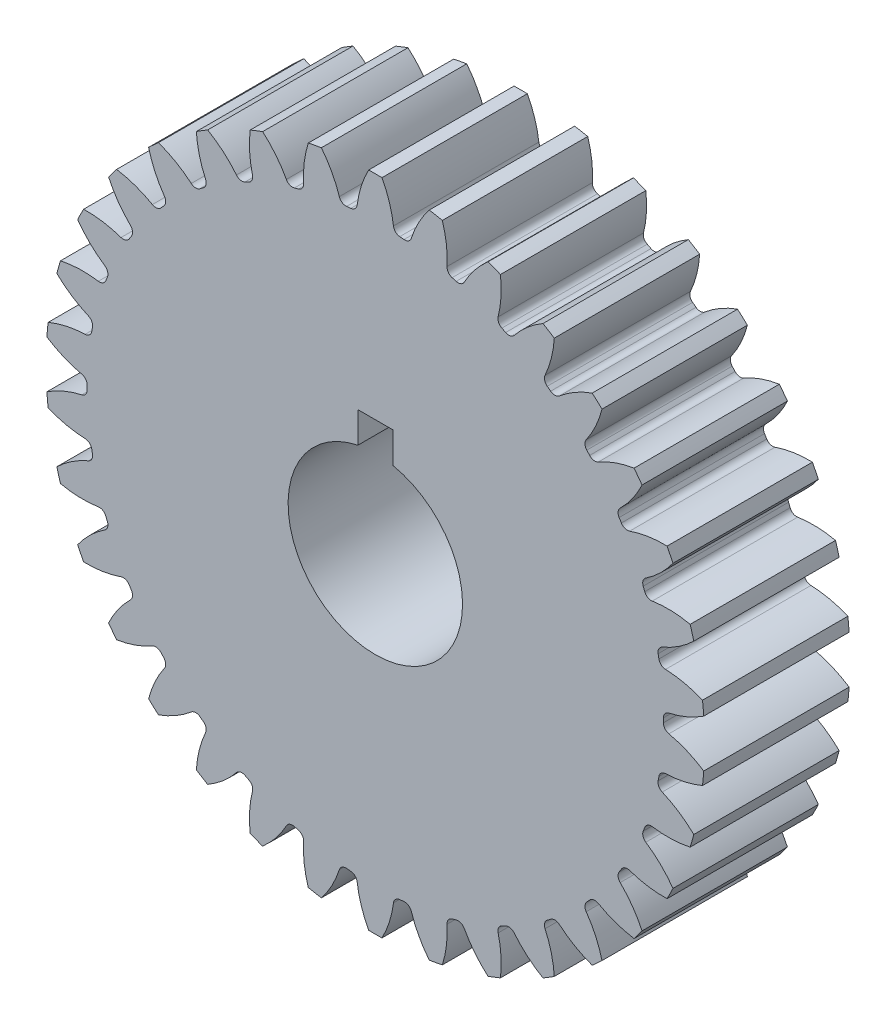
SolidWorks part; units mm, degrees
ref_plane "Front Plane" through (0, 0, 0) normal (0, 0, 1) x (1, 0, 0)
ref_plane "Top Plane" through (0, 0, 0) normal (0, 1, 0) x (1, 0, 0)
ref_plane "Right Plane" through (0, 0, 0) normal (1, 0, 0) x (0, 0, -1)
sketch "Sketch1" plane through (0, 0, 0) normal (0, 0, 1) x (1, 0, 0)
  line L0 (0, 64.998) -> (0, -63.3411) construction
  line L1 (-63.1274, 0) -> (60.8441, 0) construction
  line L2 (-2.4708, 64.998) -> (-2.4708, -63.3411) construction
  line L3 (2.4708, 64.998) -> (2.4708, -63.3411) construction
  line L4 (-2.4708, 53.4249) -> (0, 0) construction
  circle A0 centre (0, 0) radius 53.482 construction
  circle A1 centre (0, 0) radius 50.336 construction
  arc A2 (4.2073, 49.3705) -> (3.1231, 50.4096) centre (4.3089, 50.5617) cw
  arc A3 (-56.628, 0) -> (56.628, 0) centre (0, 0) ccw construction
  circle A4 centre (-1.2354, 26.7124) radius 26.741 construction
  arc A5 (-1.143, 56.6165) -> (-3.1231, 50.4096) centre (14.8024, 48.1103) ccw
  arc A6 (1.143, 56.6165) -> (3.1231, 50.4096) centre (-14.8024, 48.1103) cw
  arc A7 (1.143, 56.6165) -> (-1.143, 56.6165) centre (0, 0) ccw
  arc A8 (-4.2073, 49.3705) -> (-4.9361, 49.303) centre (0, 0) ccw
  arc A9 (-4.2073, 49.3705) -> (-3.1231, 50.4096) centre (-4.3089, 50.5617) ccw
  arc A10 (13.2075, 47.7568) -> (12.3327, 48.9774) centre (13.5262, 48.9091) cw
  arc A11 (9.2797, 55.8625) -> (6.1928, 50.1252) centre (23.3906, 44.5712) ccw
  arc A12 (11.5268, 55.4424) -> (12.3327, 48.9774) centre (-5.7102, 50.0111) cw
  arc A13 (11.5268, 55.4424) -> (9.2797, 55.8625) centre (0, 0) ccw
  arc A14 (4.9361, 49.303) -> (6.1928, 50.1252) centre (5.0552, 50.4926) ccw
  arc A15 (21.7579, 44.5168) -> (21.1222, 45.8774) centre (22.2829, 45.5909) cw
  arc A16 (19.3864, 53.2062) -> (15.2979, 48.1338) centre (31.1823, 39.5143) ccw
  arc A17 (21.518, 52.3804) -> (21.1222, 45.8774) centre (3.5766, 50.2088) cw
  arc A18 (21.518, 52.3804) -> (19.3864, 53.2062) centre (0, 0) ccw
  arc A19 (13.9115, 47.5565) -> (15.2979, 48.1338) centre (14.2471, 48.7039) ccw
  arc A20 (29.5674, 39.7608) -> (29.1925, 41.215) centre (30.2808, 40.7201) cw
  arc A21 (28.8329, 48.738) -> (23.8819, 44.5032) centre (37.9121, 33.1117) ccw
  arc A22 (30.7765, 47.5346) -> (29.1925, 41.215) centre (12.7415, 48.6967) cw
  arc A23 (30.7765, 47.5346) -> (28.8329, 48.738) centre (0, 0) ccw
  arc A24 (22.4131, 44.1906) -> (23.8819, 44.5032) centre (22.9538, 45.2568) ccw
  arc A25 (36.37, 33.6508) -> (36.2687, 35.1491) centre (37.2475, 34.4627) cw
  arc A26 (37.2976, 42.6101) -> (31.6527, 39.3572) centre (43.3508, 25.5816) ccw
  arc A27 (38.9869, 41.07) -> (36.2687, 35.1491) centre (21.4726, 45.5263) cw
  arc A28 (38.9869, 41.07) -> (37.2976, 42.6101) centre (0, 0) ccw
  arc A29 (30.1515, 39.3197) -> (31.6527, 39.3572) centre (30.8789, 40.2684) ccw
  arc A30 (41.934, 26.3949) -> (42.1098, 27.8863) centre (42.9458, 27.0317) cw
  arc A31 (44.4921, 35.0312) -> (38.3457, 32.8709) centre (47.3133, 17.1803) ccw
  arc A32 (45.8697, 33.2069) -> (42.1098, 27.8863) centre (29.4724, 40.8055) cw
  arc A33 (45.8697, 33.2069) -> (44.4921, 35.0312) centre (0, 0) ccw
  arc A34 (36.8631, 33.1099) -> (38.3457, 32.8709) centre (37.7525, 33.9088) ccw
  arc A35 (46.0701, 18.2401) -> (46.5169, 19.6738) centre (47.1816, 18.6802) cw
  arc A36 (50.1715, 26.2593) -> (43.7328, 25.2652) centre (49.6646, 8.194) ccw
  arc A37 (51.1905, 24.213) -> (46.5169, 19.6738) centre (36.4686, 34.6952) cw
  arc A38 (51.1905, 24.213) -> (50.1715, 26.2593) centre (0, 0) ccw
  arc A39 (42.3193, 25.7726) -> (43.7328, 25.2652) centre (43.3404, 26.3944) ccw
  arc A40 (48.6373, 9.4642) -> (49.3399, 10.7914) centre (49.8107, 9.6925) cw
  arc A41 (54.1424, 16.5932) -> (47.6306, 16.7991) centre (50.3246, -1.0714) ccw
  arc A42 (54.768, 14.3945) -> (49.3399, 10.7914) centre (42.2228, 27.4034) cw
  arc A43 (54.768, 14.3945) -> (54.1424, 16.5932) centre (0, 0) ccw
  arc A44 (46.3345, 17.5576) -> (47.6306, 16.7991) centre (47.4524, 17.9812) ccw
  arc A45 (49.5481, 0.3659) -> (50.4827, 1.5414) centre (50.7436, 0.3748) cw
  arc A46 (56.2695, 6.362) -> (49.9064, 7.761) centre (49.2709, -10.3002) ccw
  arc A47 (56.4804, 4.0858) -> (50.4827, 1.5414) centre (46.5393, 19.1784) cw
  arc A48 (56.4804, 4.0858) -> (56.2695, 6.362) centre (0, 0) ccw
  arc A49 (48.7717, 8.7447) -> (49.9064, 7.761) centre (49.9485, 8.9557) ccw
  arc A50 (48.7717, -8.7447) -> (49.9064, -7.761) centre (49.9485, -8.9557) cw
  arc A51 (56.4804, -4.0858) -> (50.4827, -1.5414) centre (46.5393, -19.1784) ccw
  arc A52 (56.2695, -6.362) -> (49.9064, -7.761) centre (49.2709, 10.3002) cw
  arc A53 (56.2695, -6.362) -> (56.4804, -4.0858) centre (0, 0) ccw
  arc A54 (49.5481, -0.3659) -> (50.4827, -1.5414) centre (50.7436, -0.3748) ccw
  arc A55 (46.3345, -17.5576) -> (47.6306, -16.7991) centre (47.4524, -17.9812) cw
  arc A56 (54.768, -14.3945) -> (49.3399, -10.7914) centre (42.2228, -27.4034) ccw
  arc A57 (54.1424, -16.5932) -> (47.6306, -16.7991) centre (50.3246, 1.0714) cw
  arc A58 (54.1424, -16.5932) -> (54.768, -14.3945) centre (0, 0) ccw
  arc A59 (48.6373, -9.4642) -> (49.3399, -10.7914) centre (49.8107, -9.6925) ccw
  arc A60 (42.3193, -25.7726) -> (43.7328, -25.2652) centre (43.3404, -26.3944) cw
  arc A61 (51.1905, -24.213) -> (46.5169, -19.6738) centre (36.4686, -34.6952) ccw
  arc A62 (50.1715, -26.2593) -> (43.7328, -25.2652) centre (49.6646, -8.194) cw
  arc A63 (50.1715, -26.2593) -> (51.1905, -24.213) centre (0, 0) ccw
  arc A64 (46.0701, -18.2401) -> (46.5169, -19.6738) centre (47.1816, -18.6802) ccw
  arc A65 (36.8631, -33.1099) -> (38.3457, -32.8709) centre (37.7525, -33.9088) cw
  arc A66 (45.8697, -33.2069) -> (42.1098, -27.8863) centre (29.4724, -40.8055) ccw
  arc A67 (44.4921, -35.0312) -> (38.3457, -32.8709) centre (47.3133, -17.1803) cw
  arc A68 (44.4921, -35.0312) -> (45.8697, -33.2069) centre (0, 0) ccw
  arc A69 (41.934, -26.3949) -> (42.1098, -27.8863) centre (42.9458, -27.0317) ccw
  arc A70 (30.1515, -39.3197) -> (31.6527, -39.3572) centre (30.8789, -40.2684) cw
  arc A71 (38.9869, -41.07) -> (36.2687, -35.1491) centre (21.4726, -45.5263) ccw
  arc A72 (37.2976, -42.6101) -> (31.6527, -39.3572) centre (43.3508, -25.5816) cw
  arc A73 (37.2976, -42.6101) -> (38.9869, -41.07) centre (0, 0) ccw
  arc A74 (36.37, -33.6508) -> (36.2687, -35.1491) centre (37.2475, -34.4627) ccw
  arc A75 (22.4131, -44.1906) -> (23.8819, -44.5032) centre (22.9538, -45.2568) cw
  arc A76 (30.7765, -47.5346) -> (29.1925, -41.215) centre (12.7415, -48.6967) ccw
  arc A77 (28.8329, -48.738) -> (23.8819, -44.5032) centre (37.9121, -33.1117) cw
  arc A78 (28.8329, -48.738) -> (30.7765, -47.5346) centre (0, 0) ccw
  arc A79 (29.5674, -39.7608) -> (29.1925, -41.215) centre (30.2808, -40.7201) ccw
  arc A80 (13.9115, -47.5565) -> (15.2979, -48.1338) centre (14.2471, -48.7039) cw
  arc A81 (21.518, -52.3804) -> (21.1222, -45.8774) centre (3.5766, -50.2088) ccw
  arc A82 (19.3864, -53.2062) -> (15.2979, -48.1338) centre (31.1823, -39.5143) cw
  arc A83 (19.3864, -53.2062) -> (21.518, -52.3804) centre (0, 0) ccw
  arc A84 (21.7579, -44.5168) -> (21.1222, -45.8774) centre (22.2829, -45.5909) ccw
  arc A85 (4.9361, -49.303) -> (6.1928, -50.1252) centre (5.0552, -50.4926) cw
  arc A86 (11.5268, -55.4424) -> (12.3327, -48.9774) centre (-5.7102, -50.0111) ccw
  arc A87 (9.2797, -55.8625) -> (6.1928, -50.1252) centre (23.3906, -44.5712) cw
  arc A88 (9.2797, -55.8625) -> (11.5268, -55.4424) centre (0, 0) ccw
  arc A89 (13.2075, -47.7568) -> (12.3327, -48.9774) centre (13.5262, -48.9091) ccw
  arc A90 (-4.2073, -49.3705) -> (-3.1231, -50.4096) centre (-4.3089, -50.5617) cw
  arc A91 (1.143, -56.6165) -> (3.1231, -50.4096) centre (-14.8024, -48.1103) ccw
  arc A92 (-1.143, -56.6165) -> (-3.1231, -50.4096) centre (14.8024, -48.1103) cw
  arc A93 (-1.143, -56.6165) -> (1.143, -56.6165) centre (0, 0) ccw
  arc A94 (4.2073, -49.3705) -> (3.1231, -50.4096) centre (4.3089, -50.5617) ccw
  arc A95 (-13.2075, -47.7568) -> (-12.3327, -48.9774) centre (-13.5262, -48.9091) cw
  arc A96 (-9.2797, -55.8625) -> (-6.1928, -50.1252) centre (-23.3906, -44.5712) ccw
  arc A97 (-11.5268, -55.4424) -> (-12.3327, -48.9774) centre (5.7102, -50.0111) cw
  arc A98 (-11.5268, -55.4424) -> (-9.2797, -55.8625) centre (0, 0) ccw
  arc A99 (-4.9361, -49.303) -> (-6.1928, -50.1252) centre (-5.0552, -50.4926) ccw
  arc A100 (-21.7579, -44.5168) -> (-21.1222, -45.8774) centre (-22.2829, -45.5909) cw
  arc A101 (-19.3864, -53.2062) -> (-15.2979, -48.1338) centre (-31.1823, -39.5143) ccw
  arc A102 (-21.518, -52.3804) -> (-21.1222, -45.8774) centre (-3.5766, -50.2088) cw
  arc A103 (-21.518, -52.3804) -> (-19.3864, -53.2062) centre (0, 0) ccw
  arc A104 (-13.9115, -47.5565) -> (-15.2979, -48.1338) centre (-14.2471, -48.7039) ccw
  arc A105 (-29.5674, -39.7608) -> (-29.1925, -41.215) centre (-30.2808, -40.7201) cw
  arc A106 (-28.8329, -48.738) -> (-23.8819, -44.5032) centre (-37.9121, -33.1117) ccw
  arc A107 (-30.7765, -47.5346) -> (-29.1925, -41.215) centre (-12.7415, -48.6967) cw
  arc A108 (-30.7765, -47.5346) -> (-28.8329, -48.738) centre (0, 0) ccw
  arc A109 (-22.4131, -44.1906) -> (-23.8819, -44.5032) centre (-22.9538, -45.2568) ccw
  arc A110 (-36.37, -33.6508) -> (-36.2687, -35.1491) centre (-37.2475, -34.4627) cw
  arc A111 (-37.2976, -42.6101) -> (-31.6527, -39.3572) centre (-43.3508, -25.5816) ccw
  arc A112 (-38.9869, -41.07) -> (-36.2687, -35.1491) centre (-21.4726, -45.5263) cw
  arc A113 (-38.9869, -41.07) -> (-37.2976, -42.6101) centre (0, 0) ccw
  arc A114 (-30.1515, -39.3197) -> (-31.6527, -39.3572) centre (-30.8789, -40.2684) ccw
  arc A115 (-41.934, -26.3949) -> (-42.1098, -27.8863) centre (-42.9458, -27.0317) cw
  arc A116 (-44.4921, -35.0312) -> (-38.3457, -32.8709) centre (-47.3133, -17.1803) ccw
  arc A117 (-45.8697, -33.2069) -> (-42.1098, -27.8863) centre (-29.4724, -40.8055) cw
  arc A118 (-45.8697, -33.2069) -> (-44.4921, -35.0312) centre (0, 0) ccw
  arc A119 (-36.8631, -33.1099) -> (-38.3457, -32.8709) centre (-37.7525, -33.9088) ccw
  arc A120 (-46.0701, -18.2401) -> (-46.5169, -19.6738) centre (-47.1816, -18.6802) cw
  arc A121 (-50.1715, -26.2593) -> (-43.7328, -25.2652) centre (-49.6646, -8.194) ccw
  arc A122 (-51.1905, -24.213) -> (-46.5169, -19.6738) centre (-36.4686, -34.6952) cw
  arc A123 (-51.1905, -24.213) -> (-50.1715, -26.2593) centre (0, 0) ccw
  arc A124 (-42.3193, -25.7726) -> (-43.7328, -25.2652) centre (-43.3404, -26.3944) ccw
  arc A125 (-48.6373, -9.4642) -> (-49.3399, -10.7914) centre (-49.8107, -9.6925) cw
  arc A126 (-54.1424, -16.5932) -> (-47.6306, -16.7991) centre (-50.3246, 1.0714) ccw
  arc A127 (-54.768, -14.3945) -> (-49.3399, -10.7914) centre (-42.2228, -27.4034) cw
  arc A128 (-54.768, -14.3945) -> (-54.1424, -16.5932) centre (0, 0) ccw
  arc A129 (-46.3345, -17.5576) -> (-47.6306, -16.7991) centre (-47.4524, -17.9812) ccw
  arc A130 (-49.5481, -0.3659) -> (-50.4827, -1.5414) centre (-50.7436, -0.3748) cw
  arc A131 (-56.2695, -6.362) -> (-49.9064, -7.761) centre (-49.2709, 10.3002) ccw
  arc A132 (-56.4804, -4.0858) -> (-50.4827, -1.5414) centre (-46.5393, -19.1784) cw
  arc A133 (-56.4804, -4.0858) -> (-56.2695, -6.362) centre (0, 0) ccw
  arc A134 (-48.7717, -8.7447) -> (-49.9064, -7.761) centre (-49.9485, -8.9557) ccw
  arc A135 (-48.7717, 8.7447) -> (-49.9064, 7.761) centre (-49.9485, 8.9557) cw
  arc A136 (-56.4804, 4.0858) -> (-50.4827, 1.5414) centre (-46.5393, 19.1784) ccw
  arc A137 (-56.2695, 6.362) -> (-49.9064, 7.761) centre (-49.2709, -10.3002) cw
  arc A138 (-56.2695, 6.362) -> (-56.4804, 4.0858) centre (0, 0) ccw
  arc A139 (-49.5481, 0.3659) -> (-50.4827, 1.5414) centre (-50.7436, 0.3748) ccw
  arc A140 (-46.3345, 17.5576) -> (-47.6306, 16.7991) centre (-47.4524, 17.9812) cw
  arc A141 (-54.768, 14.3945) -> (-49.3399, 10.7914) centre (-42.2228, 27.4034) ccw
  arc A142 (-54.1424, 16.5932) -> (-47.6306, 16.7991) centre (-50.3246, -1.0714) cw
  arc A143 (-54.1424, 16.5932) -> (-54.768, 14.3945) centre (0, 0) ccw
  arc A144 (-48.6373, 9.4642) -> (-49.3399, 10.7914) centre (-49.8107, 9.6925) ccw
  arc A145 (-42.3193, 25.7726) -> (-43.7328, 25.2652) centre (-43.3404, 26.3944) cw
  arc A146 (-51.1905, 24.213) -> (-46.5169, 19.6738) centre (-36.4686, 34.6952) ccw
  arc A147 (-50.1715, 26.2593) -> (-43.7328, 25.2652) centre (-49.6646, 8.194) cw
  arc A148 (-50.1715, 26.2593) -> (-51.1905, 24.213) centre (0, 0) ccw
  arc A149 (-46.0701, 18.2401) -> (-46.5169, 19.6738) centre (-47.1816, 18.6802) ccw
  arc A150 (-36.8631, 33.1099) -> (-38.3457, 32.8709) centre (-37.7525, 33.9088) cw
  arc A151 (-45.8697, 33.2069) -> (-42.1098, 27.8863) centre (-29.4724, 40.8055) ccw
  arc A152 (-44.4921, 35.0312) -> (-38.3457, 32.8709) centre (-47.3133, 17.1803) cw
  arc A153 (-44.4921, 35.0312) -> (-45.8697, 33.2069) centre (0, 0) ccw
  arc A154 (-41.934, 26.3949) -> (-42.1098, 27.8863) centre (-42.9458, 27.0317) ccw
  arc A155 (-30.1515, 39.3197) -> (-31.6527, 39.3572) centre (-30.8789, 40.2684) cw
  arc A156 (-38.9869, 41.07) -> (-36.2687, 35.1491) centre (-21.4726, 45.5263) ccw
  arc A157 (-37.2976, 42.6101) -> (-31.6527, 39.3572) centre (-43.3508, 25.5816) cw
  arc A158 (-37.2976, 42.6101) -> (-38.9869, 41.07) centre (0, 0) ccw
  arc A159 (-36.37, 33.6508) -> (-36.2687, 35.1491) centre (-37.2475, 34.4627) ccw
  arc A160 (-22.4131, 44.1906) -> (-23.8819, 44.5032) centre (-22.9538, 45.2568) cw
  arc A161 (-30.7765, 47.5346) -> (-29.1925, 41.215) centre (-12.7415, 48.6967) ccw
  arc A162 (-28.8329, 48.738) -> (-23.8819, 44.5032) centre (-37.9121, 33.1117) cw
  arc A163 (-28.8329, 48.738) -> (-30.7765, 47.5346) centre (0, 0) ccw
  arc A164 (-29.5674, 39.7608) -> (-29.1925, 41.215) centre (-30.2808, 40.7201) ccw
  arc A165 (-13.9115, 47.5565) -> (-15.2979, 48.1338) centre (-14.2471, 48.7039) cw
  arc A166 (-21.518, 52.3804) -> (-21.1222, 45.8774) centre (-3.5766, 50.2088) ccw
  arc A167 (-19.3864, 53.2062) -> (-15.2979, 48.1338) centre (-31.1823, 39.5143) cw
  arc A168 (-19.3864, 53.2062) -> (-21.518, 52.3804) centre (0, 0) ccw
  arc A169 (-21.7579, 44.5168) -> (-21.1222, 45.8774) centre (-22.2829, 45.5909) ccw
  arc A170 (-4.9361, 49.303) -> (-6.1928, 50.1252) centre (-5.0552, 50.4926) cw
  arc A171 (-11.5268, 55.4424) -> (-12.3327, 48.9774) centre (5.7102, 50.0111) ccw
  arc A172 (-9.2797, 55.8625) -> (-6.1928, 50.1252) centre (-23.3906, 44.5712) cw
  arc A173 (-9.2797, 55.8625) -> (-11.5268, 55.4424) centre (0, 0) ccw
  arc A174 (-13.2075, 47.7568) -> (-12.3327, 48.9774) centre (-13.5262, 48.9091) ccw
  arc A175 (4.9361, 49.303) -> (4.2073, 49.3705) centre (0, 0) ccw
  arc A176 (13.9115, 47.5565) -> (13.2075, 47.7568) centre (0, 0) ccw
  arc A177 (-13.2075, 47.7568) -> (-13.9115, 47.5565) centre (0, 0) ccw
  arc A178 (-21.7579, 44.5168) -> (-22.4131, 44.1906) centre (0, 0) ccw
  arc A179 (-29.5674, 39.7608) -> (-30.1515, 39.3197) centre (0, 0) ccw
  arc A180 (-36.37, 33.6508) -> (-36.8631, 33.1099) centre (0, 0) ccw
  arc A181 (-41.934, 26.3949) -> (-42.3193, 25.7726) centre (0, 0) ccw
  arc A182 (-46.0701, 18.2401) -> (-46.3345, 17.5576) centre (0, 0) ccw
  arc A183 (-48.6373, 9.4642) -> (-48.7717, 8.7447) centre (0, 0) ccw
  arc A184 (-49.5481, 0.3659) -> (-49.5481, -0.3659) centre (0, 0) ccw
  arc A185 (-48.7717, -8.7447) -> (-48.6373, -9.4642) centre (0, 0) ccw
  arc A186 (-46.3345, -17.5576) -> (-46.0701, -18.2401) centre (0, 0) ccw
  arc A187 (-42.3193, -25.7726) -> (-41.934, -26.3949) centre (0, 0) ccw
  arc A188 (-36.8631, -33.1099) -> (-36.37, -33.6508) centre (0, 0) ccw
  arc A189 (-30.1515, -39.3197) -> (-29.5674, -39.7608) centre (0, 0) ccw
  arc A190 (-22.4131, -44.1906) -> (-21.7579, -44.5168) centre (0, 0) ccw
  arc A191 (-13.9115, -47.5565) -> (-13.2075, -47.7568) centre (0, 0) ccw
  arc A192 (-4.9361, -49.303) -> (-4.2073, -49.3705) centre (0, 0) ccw
  arc A193 (4.2073, -49.3705) -> (4.9361, -49.303) centre (0, 0) ccw
  arc A194 (21.7579, -44.5168) -> (22.4131, -44.1906) centre (0, 0) ccw
  arc A195 (13.2075, -47.7568) -> (13.9115, -47.5565) centre (0, 0) ccw
  arc A196 (36.37, -33.6508) -> (36.8631, -33.1099) centre (0, 0) ccw
  arc A197 (29.5674, -39.7608) -> (30.1515, -39.3197) centre (0, 0) ccw
  arc A198 (41.934, -26.3949) -> (42.3193, -25.7726) centre (0, 0) ccw
  arc A199 (48.6373, -9.4642) -> (48.7717, -8.7447) centre (0, 0) ccw
  arc A200 (46.0701, -18.2401) -> (46.3345, -17.5576) centre (0, 0) ccw
  arc A201 (48.7717, 8.7447) -> (48.6373, 9.4642) centre (0, 0) ccw
  arc A202 (49.5481, -0.3659) -> (49.5481, 0.3659) centre (0, 0) ccw
  arc A203 (46.3345, 17.5576) -> (46.0701, 18.2401) centre (0, 0) ccw
  arc A204 (42.3193, 25.7726) -> (41.934, 26.3949) centre (0, 0) ccw
  arc A205 (36.8631, 33.1099) -> (36.37, 33.6508) centre (0, 0) ccw
  arc A206 (30.1515, 39.3197) -> (29.5674, 39.7608) centre (0, 0) ccw
  arc A207 (22.4131, 44.1906) -> (21.7579, 44.5168) centre (0, 0) ccw
  point P14 (-2.4708, 53.4249)
  point P18 (14.8024, 48.1103)
  point P27 (3.2206, 49.4447)
  point P30 (-3.2206, 49.4447)
  point P35 (7.388, 52.9693)
  point P46 (16.9953, 50.7098)
  point P57 (26.0238, 46.7235)
  point P68 (34.1661, 41.1461)
  point P79 (41.145, 34.1675)
  point P90 (46.7227, 26.0253)
  point P101 (50.7093, 16.9969)
  point P112 (52.969, 7.3897)
  point P123 (53.425, -2.4691)
  point P134 (52.0616, -12.2439)
  point P145 (48.9254, -21.6017)
  point P156 (44.123, -30.2239)
  point P167 (37.8181, -37.8169)
  point P178 (30.2253, -44.122)
  point P189 (21.6033, -48.9247)
  point P200 (12.2456, -52.0612)
  point P211 (2.4708, -53.4249)
  point P222 (-7.388, -52.9693)
  point P233 (-16.9953, -50.7098)
  point P244 (-26.0238, -46.7235)
  point P255 (-34.1661, -41.1461)
  point P266 (-41.145, -34.1675)
  point P277 (-46.7227, -26.0253)
  point P288 (-50.7093, -16.9969)
  point P299 (-52.969, -7.3897)
  point P310 (-53.425, 2.4691)
  point P321 (-52.0616, 12.2439)
  point P332 (-48.9254, 21.6017)
  point P343 (-44.123, 30.2239)
  point P354 (-37.8181, 37.8169)
  point P365 (-30.2253, 44.122)
  point P376 (-21.6033, 48.9247)
  point P387 (-12.2456, 52.0612)
  point P396 (0, 0)
  dimension "D1" = 113.256
  dimension "D2" = 106.964
  dimension "D3" = 100.672
  dimension "D4" = 1.1955
  dimension "D5" = 2.4708
  dimension "D6" = 2.4708
  dimension "D7" = 34
extrude "Boss-Extrude1" add sketch "Sketch1" along normal mid plane 25
sketch "Sketch2" plane through (0, 0, -12.5) normal (0, 0, -1) x (-1, 0, 0)
  circle A0 centre (0, 0) radius 15
  dimension "D1" = 30
extrude "Cut-Extrude2" cut sketch "Sketch2" against normal through all
sketch "Sketch3" plane through (0, 0, 12.5) normal (0, 0, 1) x (1, 0, 0)
  line L0 (-3, 0) -> (3, 0)
  line L1 (3, 0) -> (3, 20)
  line L2 (-3, 0) -> (-3, 20)
  line L3 (3, 20) -> (-3, 20)
  dimension "D3" = 20
extrude "Cut-Extrude3" cut sketch "Sketch3" against normal through all
